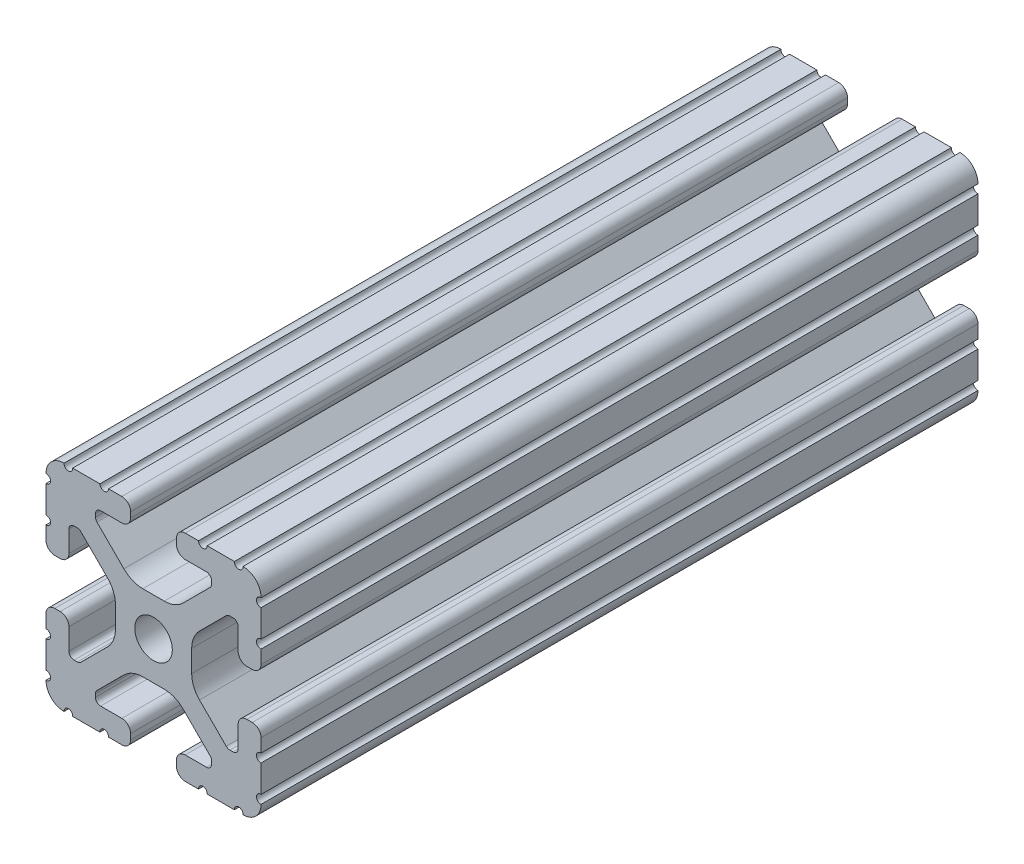
SolidWorks part; units mm, degrees
material "6061 Alloy"
ref_plane "Front Plane" through (0, 0, 0) normal (0, 0, 1) x (1, 0, 0)
ref_plane "Top Plane" through (0, 0, 0) normal (0, 1, 0) x (1, 0, 0)
ref_plane "Right Plane" through (0, 0, 0) normal (1, 0, 0) x (0, 0, -1)
sketch "Sketch1" plane through (0, 0, 0) normal (0, 0, 1) x (1, 0, 0)
  line L0 (0, 25.6181) -> (0, -24.623) construction
  line L1 (-20.8943, 0) -> (20.4607, 0) construction
  line L2 (-10.0229, 12.9148) -> (-5.2522, 8.144)
  line L3 (-10.287, 14.0843) -> (-10.287, 13.5524)
  line L4 (-5.6176, 14.986) -> (-9.3853, 14.986)
  line L5 (-4.064, 17.4964) -> (-4.064, 16.5396)
  line L6 (-7.9742, 19.05) -> (-5.6176, 19.05)
  line L7 (-14.3277, 19.05) -> (-9.4982, 19.05)
  line L8 (-19.05, 9.4961) -> (-19.05, 14.3277)
  line L9 (-19.05, 5.6176) -> (-19.05, 7.9763)
  line L10 (-16.5396, 4.064) -> (-17.4964, 4.064)
  line L11 (-14.986, 9.3853) -> (-14.986, 5.6176)
  line L12 (-13.516, 10.287) -> (-14.0843, 10.287)
  line L13 (-8.1476, 5.2921) -> (-12.8784, 10.0229)
  line L14 (-6.7564, -1.9335) -> (-6.7564, 1.9335)
  line L15 (-12.8784, -10.0229) -> (-8.1476, -5.2921)
  line L16 (-14.0843, -10.287) -> (-13.516, -10.287)
  line L17 (-14.986, -5.6176) -> (-14.986, -9.3853)
  line L18 (-17.4964, -4.064) -> (-16.5396, -4.064)
  line L19 (-19.05, -7.9763) -> (-19.05, -5.6176)
  line L20 (-19.05, -14.3277) -> (-19.05, -9.4961)
  line L21 (-9.4961, -19.05) -> (-14.3277, -19.05)
  line L22 (-5.6176, -19.05) -> (-7.9763, -19.05)
  line L23 (-4.064, -17.4964) -> (-4.064, -16.5396)
  line L24 (10.0229, -12.9148) -> (5.2522, -8.144)
  line L25 (10.287, -14.0843) -> (10.287, -13.5524)
  line L26 (5.6176, -14.986) -> (9.3853, -14.986)
  line L28 (-1.9022, 6.7564) -> (1.9022, 6.7564)
  line L29 (-1.9022, -6.7564) -> (1.9022, -6.7564)
  line L31 (-5.6176, -14.986) -> (-9.3853, -14.986)
  line L32 (-10.287, -14.0843) -> (-10.287, -13.5524)
  line L33 (-10.0229, -12.9148) -> (-5.2522, -8.144)
  line L66 (4.064, -16.5396) -> (4.064, -17.4964)
  line L67 (5.6176, -19.05) -> (7.9763, -19.05)
  line L68 (9.4961, -19.05) -> (14.3277, -19.05)
  line L69 (19.05, -14.3277) -> (19.05, -9.4961)
  line L70 (19.05, -7.9763) -> (19.05, -5.6176)
  line L71 (17.4964, -4.064) -> (16.5396, -4.064)
  line L72 (14.986, -5.6176) -> (14.986, -9.3853)
  line L73 (14.0843, -10.287) -> (13.516, -10.287)
  line L74 (12.8784, -10.0229) -> (8.1476, -5.2921)
  line L75 (6.7564, -1.9335) -> (6.7564, 1.9335)
  line L76 (8.1476, 5.2921) -> (12.8784, 10.0229)
  line L77 (13.516, 10.287) -> (14.0843, 10.287)
  line L78 (14.986, 9.3853) -> (14.986, 5.6176)
  line L79 (16.5396, 4.064) -> (17.4964, 4.064)
  line L80 (19.05, 5.6176) -> (19.05, 7.9763)
  line L81 (19.05, 9.4961) -> (19.05, 14.3277)
  line L82 (14.3277, 19.05) -> (9.4982, 19.05)
  line L83 (7.9742, 19.05) -> (5.6176, 19.05)
  line L84 (4.064, 17.4964) -> (4.064, 16.5396)
  line L85 (5.6176, 14.986) -> (9.3853, 14.986)
  line L86 (10.287, 14.0843) -> (10.287, 13.5524)
  line L87 (10.0229, 12.9148) -> (5.2522, 8.144)
  arc A0 (-10.0229, 12.9148) -> (-10.287, 13.5524) centre (-9.3853, 13.5524) cw
  circle A1 centre (0, 0) radius 3.3274
  arc A2 (-10.287, 14.0843) -> (-9.3853, 14.986) centre (-9.3853, 14.0843) cw
  arc A3 (-4.064, 16.5396) -> (-5.6176, 14.986) centre (-5.6176, 16.5396) cw
  arc A4 (-5.6176, 19.05) -> (-4.064, 17.4964) centre (-5.6176, 17.4964) cw
  arc A5 (-7.9742, 19.05) -> (-9.4982, 19.05) centre (-8.7362, 19.05) cw
  arc A6 (-14.3277, 19.05) -> (-15.8475, 19.05) centre (-15.0876, 18.9933) cw
  arc A7 (-19.05, 15.8475) -> (-15.8475, 19.05) centre (-15.8751, 15.8751) cw
  arc A8 (-19.05, 15.8475) -> (-19.05, 14.3277) centre (-18.9933, 15.0876) cw
  arc A9 (-19.05, 9.4961) -> (-19.05, 7.9763) centre (-18.9933, 8.7362) cw
  arc A10 (-17.4964, 4.064) -> (-19.05, 5.6176) centre (-17.4964, 5.6176) cw
  arc A11 (-14.986, 5.6176) -> (-16.5396, 4.064) centre (-16.5396, 5.6176) cw
  arc A12 (-14.986, 9.3853) -> (-14.0843, 10.287) centre (-14.0843, 9.3853) cw
  arc A13 (-13.516, 10.287) -> (-12.8784, 10.0229) centre (-13.516, 9.3853) cw
  arc A14 (-8.1476, 5.2921) -> (-6.7564, 1.9335) centre (-11.5062, 1.9335) cw
  arc A15 (-6.7564, -1.9335) -> (-8.1476, -5.2921) centre (-11.5062, -1.9335) cw
  arc A16 (-12.8784, -10.0229) -> (-13.516, -10.287) centre (-13.516, -9.3853) cw
  arc A17 (-14.0843, -10.287) -> (-14.986, -9.3853) centre (-14.0843, -9.3853) cw
  arc A18 (-16.5396, -4.064) -> (-14.986, -5.6176) centre (-16.5396, -5.6176) cw
  arc A19 (-19.05, -5.6176) -> (-17.4964, -4.064) centre (-17.4964, -5.6176) cw
  arc A20 (-19.05, -7.9763) -> (-19.05, -9.4961) centre (-18.9933, -8.7362) cw
  arc A21 (-19.05, -14.3277) -> (-19.05, -15.8475) centre (-18.9933, -15.0876) cw
  arc A22 (-15.8475, -19.05) -> (-19.05, -15.8475) centre (-15.8751, -15.8751) cw
  arc A23 (-15.8475, -19.05) -> (-14.3277, -19.05) centre (-15.0876, -18.9933) cw
  arc A24 (-9.4961, -19.05) -> (-7.9763, -19.05) centre (-8.7362, -18.9933) cw
  arc A25 (-4.064, -17.4964) -> (-5.6176, -19.05) centre (-5.6176, -17.4964) cw
  arc A26 (-5.2522, -8.144) -> (-1.9022, -6.7564) centre (-1.9022, -11.494) cw
  arc A27 (1.9022, -6.7564) -> (5.2522, -8.144) centre (1.9022, -11.494) cw
  arc A28 (10.0229, -12.9148) -> (10.287, -13.5524) centre (9.3853, -13.5524) cw
  arc A29 (10.287, -14.0843) -> (9.3853, -14.986) centre (9.3853, -14.0843) cw
  arc A30 (4.064, -16.5396) -> (5.6176, -14.986) centre (5.6176, -16.5396) cw
  arc A31 (-4.064, -16.5396) -> (-5.6176, -14.986) centre (-5.6176, -16.5396) ccw
  arc A32 (-10.287, -14.0843) -> (-9.3853, -14.986) centre (-9.3853, -14.0843) ccw
  arc A33 (-10.0229, -12.9148) -> (-10.287, -13.5524) centre (-9.3853, -13.5524) ccw
  arc A79 (4.064, -17.4964) -> (5.6176, -19.05) centre (5.6176, -17.4964) ccw
  arc A80 (9.4961, -19.05) -> (7.9763, -19.05) centre (8.7362, -18.9933) ccw
  arc A81 (15.8475, -19.05) -> (14.3277, -19.05) centre (15.0876, -18.9933) ccw
  arc A82 (15.8475, -19.05) -> (19.05, -15.8475) centre (15.8751, -15.8751) ccw
  arc A83 (19.05, -14.3277) -> (19.05, -15.8475) centre (18.9933, -15.0876) ccw
  arc A84 (19.05, -7.9763) -> (19.05, -9.4961) centre (18.9933, -8.7362) ccw
  arc A85 (19.05, -5.6176) -> (17.4964, -4.064) centre (17.4964, -5.6176) ccw
  arc A86 (16.5396, -4.064) -> (14.986, -5.6176) centre (16.5396, -5.6176) ccw
  arc A87 (14.0843, -10.287) -> (14.986, -9.3853) centre (14.0843, -9.3853) ccw
  arc A88 (12.8784, -10.0229) -> (13.516, -10.287) centre (13.516, -9.3853) ccw
  arc A89 (6.7564, -1.9335) -> (8.1476, -5.2921) centre (11.5062, -1.9335) ccw
  arc A90 (8.1476, 5.2921) -> (6.7564, 1.9335) centre (11.5062, 1.9335) ccw
  arc A91 (13.516, 10.287) -> (12.8784, 10.0229) centre (13.516, 9.3853) ccw
  arc A92 (14.986, 9.3853) -> (14.0843, 10.287) centre (14.0843, 9.3853) ccw
  arc A93 (14.986, 5.6176) -> (16.5396, 4.064) centre (16.5396, 5.6176) ccw
  arc A94 (17.4964, 4.064) -> (19.05, 5.6176) centre (17.4964, 5.6176) ccw
  arc A95 (19.05, 9.4961) -> (19.05, 7.9763) centre (18.9933, 8.7362) ccw
  arc A96 (19.05, 15.8475) -> (19.05, 14.3277) centre (18.9933, 15.0876) ccw
  arc A97 (19.05, 15.8475) -> (15.8475, 19.05) centre (15.8751, 15.8751) ccw
  arc A98 (14.3277, 19.05) -> (15.8475, 19.05) centre (15.0876, 18.9933) ccw
  arc A99 (7.9742, 19.05) -> (9.4982, 19.05) centre (8.7362, 19.05) ccw
  arc A100 (5.6176, 19.05) -> (4.064, 17.4964) centre (5.6176, 17.4964) ccw
  arc A101 (4.064, 16.5396) -> (5.6176, 14.986) centre (5.6176, 16.5396) ccw
  arc A102 (10.287, 14.0843) -> (9.3853, 14.986) centre (9.3853, 14.0843) ccw
  arc A103 (10.0229, 12.9148) -> (10.287, 13.5524) centre (9.3853, 13.5524) ccw
  arc A104 (1.9022, 6.7564) -> (5.2522, 8.144) centre (1.9022, 11.494) ccw
  arc A105 (-5.2522, 8.144) -> (-1.9022, 6.7564) centre (-1.9022, 11.494) ccw
  dimension "D1" = 6.6548
  dimension "D2" = 19.05
  dimension "D3" = 38.1
  dimension "D4" = 20.574
  dimension "D5" = 13.5128
  dimension "D6" = 4.064
  dimension "D7" = 8.128
  dimension "D8" = 4.064
  dimension "D9" = 12.2936
extrude "Extrude1" add sketch "Sketch1" against normal blind 127
